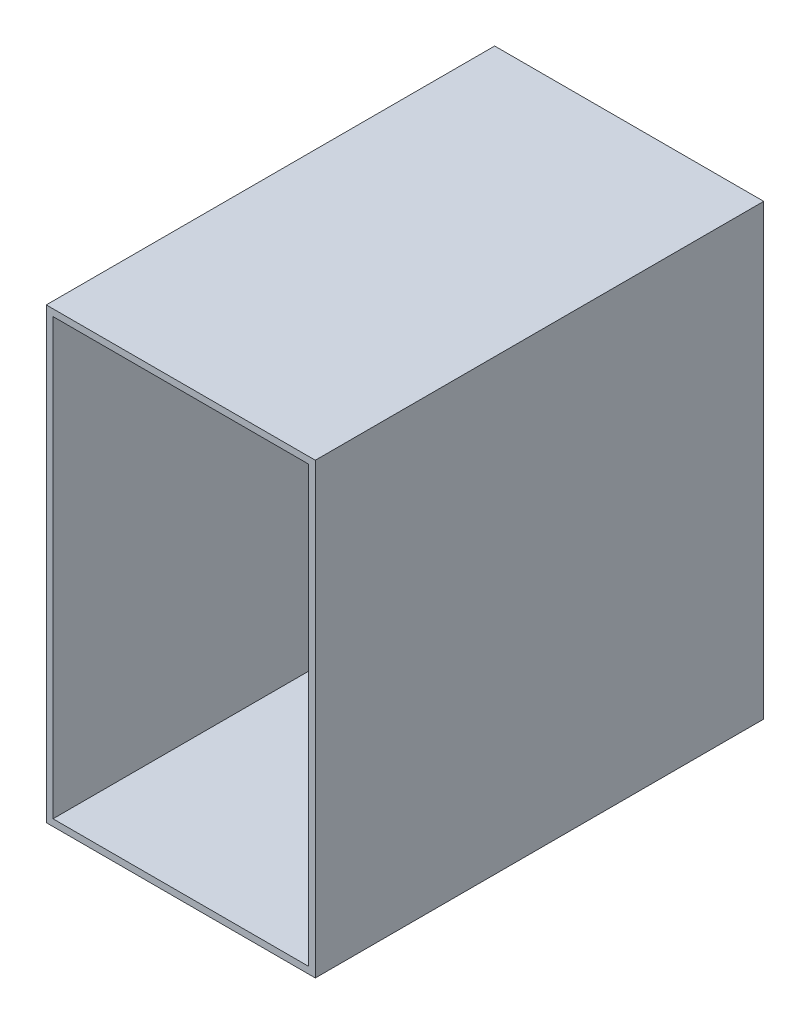
SolidWorks part; units mm, degrees
ref_plane "Alzado" through (0, 0, 0) normal (0, 0, 1) x (1, 0, 0)
ref_plane "Planta" through (0, 0, 0) normal (0, 1, 0) x (1, 0, 0)
ref_plane "Vista lateral" through (0, 0, 0) normal (1, 0, 0) x (0, 0, -1)
sketch "Croquis2" plane through (0, 0, 0) normal (0, 0, 1) x (1, 0, 0)
  line L1 (0, 0) -> (120, 0)
  line L2 (0, 0) -> (0, 200)
  line L3 (0, 200) -> (120, 200)
  line L4 (120, 0) -> (120, 200)
  dimension "D1" = 120
  dimension "D2" = 200
extrude "Saliente-Extruir1" add sketch "Croquis2" along normal blind 200
ref_plane "Plano1" through (120, 0, 0) normal (1, 0, 0) x (0, 0, -1)
sketch "Croquis3" plane through (120, 0, 0) normal (1, 0, 0) x (0, 0, -1)
  line L0 (0, 0) -> (0, 200) construction
  line L1 (-200, 200) -> (0, 200) construction
  circle A0 centre (-100, 100) radius 85 construction
  point P2 (-99.0255, 98.5383)
  point P5 (0, 100)
  point P8 (-100, 200)
  point P9 (0, 0)
  dimension "D1" = 170
shell "Vaciado1" thickness 3
sketch "Croquis4" plane through (117, 0, 0) normal (-1, 0, 0) x (0, 0, 1)
  circle A0 centre (100, 100) radius 10
  dimension "D1" = 20
extrude "Saliente-Extruir2" add sketch "Croquis4" along normal blind 80
